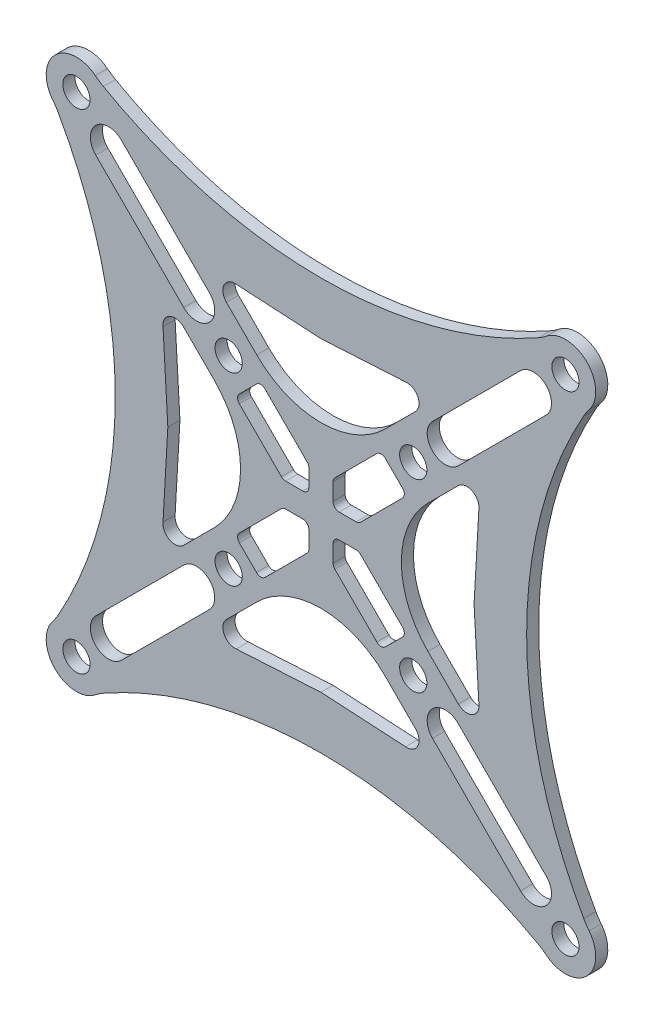
SolidWorks part; units mm, degrees
material "Thornel Mat VMA"
ref_plane "前视基准面" through (0, 0, 0) normal (0, 0, 1) x (1, 0, 0)
ref_plane "上视基准面" through (0, 0, 0) normal (0, 1, 0) x (1, 0, 0)
ref_plane "右视基准面" through (0, 0, 0) normal (1, 0, 0) x (0, 0, -1)
sketch "草图1" plane through (0, 0, 0) normal (0, 0, 1) x (1, 0, 0)
  line L0 (-2.3574, 13.9739) -> (-7.3762, 8.9551)
  line L1 (4.6665, 38.0627) -> (3.2523, 36.6485)
  line L2 (3.2523, 36.6485) -> (1.8381, 35.2343)
  line L3 (1.8381, 33.8201) -> (2.1916, 33.4665)
  line L4 (2.1916, 33.4665) -> (4.9992, 30.659)
  line L5 (4.9992, 30.659) -> (8.7848, 26.8734)
  line L6 (9.4919, 26.5805) -> (12.3203, 26.5805)
  line L7 (13.3203, 27.5805) -> (13.3203, 30.4089)
  line L8 (13.0274, 31.116) -> (9.2418, 34.9016)
  line L9 (9.2418, 34.9016) -> (6.4343, 37.7092)
  line L10 (6.4343, 37.7092) -> (6.0807, 38.0627)
  line L11 (4.6665, 11.0983) -> (3.2523, 12.5125)
  line L12 (3.2523, 12.5125) -> (1.8381, 13.9267)
  line L13 (1.8381, 15.3409) -> (2.1916, 15.6945)
  line L14 (2.1916, 15.6945) -> (4.9992, 18.5021)
  line L15 (4.9992, 18.5021) -> (8.7848, 22.2876)
  line L16 (9.4919, 22.5805) -> (12.3203, 22.5805)
  line L17 (13.3203, 21.5805) -> (13.3203, 18.7521)
  line L18 (13.0274, 18.045) -> (9.2418, 14.2594)
  line L19 (9.2418, 14.2594) -> (6.4343, 11.4518)
  line L20 (6.4343, 11.4518) -> (6.0807, 11.0983)
  line L21 (-3.1117, 1.9059) -> (-17.6553, -12.6377)
  line L22 (-21.898, -8.3951) -> (-7.3543, 6.1485)
  line L23 (-2.3574, 35.1871) -> (-7.3762, 40.2059)
  line L24 (-0.3051, 1.884) -> (4.7137, 6.9028)
  line L25 (52.5385, 57.5561) -> (37.9949, 43.0125)
  line L26 (33.7523, 47.2551) -> (48.2959, 61.7988)
  line L27 (30.9457, 1.884) -> (25.9269, 6.9028)
  line L28 (25.9741, 11.0983) -> (27.3883, 12.5125)
  line L29 (27.3883, 12.5125) -> (28.8025, 13.9267)
  line L30 (28.8025, 15.3409) -> (28.449, 15.6945)
  line L31 (28.449, 15.6945) -> (25.6414, 18.5021)
  line L32 (25.6414, 18.5021) -> (21.8558, 22.2876)
  line L33 (21.1487, 22.5805) -> (18.3203, 22.5805)
  line L34 (17.3203, 21.5805) -> (17.3203, 18.7521)
  line L35 (17.6132, 18.045) -> (21.3987, 14.2594)
  line L36 (21.3987, 14.2594) -> (24.2063, 11.4518)
  line L37 (24.2063, 11.4518) -> (24.5599, 11.0983)
  line L38 (37.9949, 6.1485) -> (52.5385, -8.3951)
  line L39 (48.2959, -12.6377) -> (33.7523, 1.9059)
  line L40 (32.998, 13.9739) -> (38.0168, 8.9551)
  line L41 (21.3987, 34.9016) -> (24.2063, 37.7092)
  line L42 (24.2063, 37.7092) -> (24.5599, 38.0627)
  line L43 (25.9741, 38.0627) -> (27.3883, 36.6485)
  line L44 (27.3883, 36.6485) -> (28.8025, 35.2343)
  line L45 (28.8025, 33.8201) -> (28.449, 33.4665)
  line L46 (28.449, 33.4665) -> (25.6414, 30.659)
  line L47 (25.6414, 30.659) -> (21.8558, 26.8734)
  line L48 (21.1487, 26.5805) -> (18.3203, 26.5805)
  line L49 (17.3203, 27.5805) -> (17.3203, 30.4089)
  line L50 (17.6132, 31.116) -> (21.3987, 34.9016)
  line L51 (32.998, 35.1871) -> (38.0168, 40.2059)
  line L52 (-0.3051, 47.277) -> (4.7137, 42.2582)
  line L53 (30.9457, 47.277) -> (25.9269, 42.2582)
  line L54 (-7.3543, 43.0125) -> (-21.898, 57.5561)
  line L55 (-17.6553, 61.7988) -> (-3.1117, 47.2551)
  arc A0 (1.8381, 35.2343) -> (1.8381, 33.8201) centre (2.5452, 34.5272) ccw
  arc A1 (8.7848, 26.8734) -> (9.4919, 26.5805) centre (9.4919, 27.5805) ccw
  arc A2 (12.3203, 26.5805) -> (13.3203, 27.5805) centre (12.3203, 27.5805) ccw
  arc A3 (13.3203, 30.4089) -> (13.0274, 31.116) centre (12.3203, 30.4089) ccw
  arc A4 (6.0807, 38.0627) -> (4.6665, 38.0627) centre (5.3736, 37.3556) ccw
  circle A5 centre (-25.0799, -15.8197) radius 2.25
  arc A6 (1.8381, 15.3409) -> (1.8381, 13.9267) centre (2.5452, 14.6338) ccw
  arc A7 (9.4919, 22.5805) -> (8.7848, 22.2876) centre (9.4919, 21.5805) ccw
  arc A8 (13.3203, 21.5805) -> (12.3203, 22.5805) centre (12.3203, 21.5805) ccw
  arc A9 (13.0274, 18.045) -> (13.3203, 18.7521) centre (12.3203, 18.7521) ccw
  arc A10 (4.6665, 11.0983) -> (6.0807, 11.0983) centre (5.3736, 11.8054) ccw
  arc A11 (-21.898, -8.3951) -> (-17.6553, -12.6377) centre (-19.7766, -10.5164) ccw
  arc A12 (-3.1117, 1.9059) -> (-7.3543, 6.1485) centre (-5.233, 4.0272) ccw
  arc A13 (-28.9897, -12.7031) -> (-21.9633, -19.7295) centre (-25.0799, -15.8197) ccw
  arc A14 (15.3203, 11.2962) -> (4.7137, 6.9028) centre (15.3203, -3.7038) ccw
  arc A15 (-0.3051, 1.884) -> (1.3391, -1.5169) centre (1.1091, 0.4698) ccw
  arc A16 (-10.7771, 10.5993) -> (-7.3762, 8.9551) centre (-8.7904, 10.3693) ccw
  circle A17 centre (0.0703, 9.3305) radius 2.25
  arc A18 (2.036, 24.5805) -> (-2.3574, 35.1871) centre (-12.964, 24.5805) ccw
  arc A19 (-2.3574, 13.9739) -> (2.036, 24.5805) centre (-12.964, 24.5805) ccw
  arc A20 (52.5385, 57.5561) -> (48.2959, 61.7988) centre (50.4172, 59.6774) ccw
  arc A21 (33.7523, 47.2551) -> (37.9949, 43.0125) centre (35.8736, 45.1338) ccw
  arc A22 (38.0168, 8.9551) -> (41.4177, 10.5993) centre (39.431, 10.3693) ccw
  arc A23 (25.9269, 6.9028) -> (15.3203, 11.2962) centre (15.3203, -3.7038) ccw
  arc A24 (28.8025, 13.9267) -> (28.8025, 15.3409) centre (28.0954, 14.6338) ccw
  arc A25 (21.8558, 22.2876) -> (21.1487, 22.5805) centre (21.1487, 21.5805) ccw
  arc A26 (18.3203, 22.5805) -> (17.3203, 21.5805) centre (18.3203, 21.5805) ccw
  arc A27 (17.3203, 18.7521) -> (17.6132, 18.045) centre (18.3203, 18.7521) ccw
  arc A28 (24.5599, 11.0983) -> (25.9741, 11.0983) centre (25.267, 11.8054) ccw
  arc A29 (29.3015, -1.5169) -> (30.9457, 1.884) centre (29.5315, 0.4698) ccw
  arc A30 (48.2959, -12.6377) -> (52.5385, -8.3951) centre (50.4172, -10.5164) ccw
  arc A31 (37.9949, 6.1485) -> (33.7523, 1.9059) centre (35.8736, 4.0272) ccw
  circle A32 centre (30.5703, 9.3305) radius 2.25
  circle A33 centre (55.7205, -15.8197) radius 2.25
  arc A34 (52.6039, -19.7295) -> (59.6303, -12.7031) centre (55.7205, -15.8197) ccw
  arc A35 (25.9741, 38.0627) -> (24.5599, 38.0627) centre (25.267, 37.3556) ccw
  arc A36 (28.8025, 33.8201) -> (28.8025, 35.2343) centre (28.0954, 34.5272) ccw
  arc A37 (21.1487, 26.5805) -> (21.8558, 26.8734) centre (21.1487, 27.5805) ccw
  arc A38 (17.3203, 27.5805) -> (18.3203, 26.5805) centre (18.3203, 27.5805) ccw
  arc A39 (17.6132, 31.116) -> (17.3203, 30.4089) centre (18.3203, 30.4089) ccw
  arc A40 (32.998, 35.1871) -> (28.6046, 24.5805) centre (43.6046, 24.5805) ccw
  arc A41 (28.6046, 24.5805) -> (32.998, 13.9739) centre (43.6046, 24.5805) ccw
  circle A42 centre (55.7205, 64.9807) radius 2.25
  arc A43 (-17.6553, 61.7988) -> (-21.898, 57.5561) centre (-19.7766, 59.6774) ccw
  arc A44 (-7.3543, 43.0125) -> (-3.1117, 47.2551) centre (-5.233, 45.1338) ccw
  circle A45 centre (30.5703, 39.8305) radius 2.25
  arc A46 (59.6303, 61.8641) -> (52.6039, 68.8905) centre (55.7205, 64.9807) ccw
  arc A47 (-7.3762, 40.2059) -> (-10.7771, 38.5617) centre (-8.7904, 38.7917) ccw
  arc A48 (30.9457, 47.277) -> (29.3015, 50.6779) centre (29.5315, 48.6912) ccw
  arc A49 (4.7137, 42.2582) -> (15.3203, 37.8648) centre (15.3203, 52.8648) ccw
  arc A50 (15.3203, 37.8648) -> (25.9269, 42.2582) centre (15.3203, 52.8648) ccw
  circle A51 centre (0.0703, 39.8305) radius 2.25
  arc A52 (1.3391, 50.6779) -> (-0.3051, 47.277) centre (1.1091, 48.6912) ccw
  arc A53 (-21.9633, 68.8905) -> (-28.9897, 61.8641) centre (-25.0799, 64.9807) ccw
  arc A54 (41.4177, 38.5617) -> (38.0168, 40.2059) centre (39.431, 38.7917) ccw
  circle A55 centre (-25.0799, 64.9807) radius 2.25
  arc A56 (-28.0953, -11.3755) -> (-28.0953, 60.5365) centre (-91.9643, 24.5805) ccw
  arc A57 (51.2763, -18.8351) -> (-20.6357, -18.8351) centre (15.3203, -82.704) ccw
  arc A58 (-20.6357, 67.9961) -> (51.2763, 67.9961) centre (15.3203, 131.8651) ccw
  arc A59 (-21.9633, 68.8905) -> (-20.6357, 67.9961) centre (-15.73, 76.7102) ccw
  arc A60 (-28.0953, 60.5365) -> (-28.9897, 61.8641) centre (-36.8094, 55.6308) ccw
  arc A61 (-28.9897, -12.7031) -> (-28.0953, -11.3755) centre (-36.8094, -6.4698) ccw
  arc A62 (-20.6357, -18.8351) -> (-21.9633, -19.7295) centre (-15.73, -27.5491) ccw
  arc A63 (51.2763, 67.9961) -> (52.6039, 68.8905) centre (46.3706, 76.7102) ccw
  arc A64 (59.6303, 61.8641) -> (58.7359, 60.5365) centre (67.4499, 55.6308) ccw
  arc A65 (52.6039, -19.7295) -> (51.2763, -18.8351) centre (46.3706, -27.5491) ccw
  arc A66 (58.7359, -11.3755) -> (59.6303, -12.7031) centre (67.4499, -6.4698) ccw
  arc A67 (58.7359, 60.5365) -> (58.7359, -11.3755) centre (122.6048, 24.5805) ccw
  spline S0 degree 3 poles (1.3391, -1.5169) (5.9995, -1.2512) (10.6599, -0.9854) (15.3203, -0.7197) knots 0 0 0 0 1.400387 1.400387 1.400387 1.400387
  spline S1 degree 3 poles (-10.7771, 38.5617) (-10.5114, 33.9013) (-10.2456, 29.2409) (-9.9799, 24.5805) knots 0 0 0 0 1.400387 1.400387 1.400387 1.400387
  spline S2 degree 3 poles (-10.7771, 10.5993) (-10.5114, 15.2597) (-10.2456, 19.9201) (-9.9799, 24.5805) knots 0 0 0 0 1.400387 1.400387 1.400387 1.400387
  spline S3 degree 3 poles (29.3015, -1.5169) (24.6411, -1.2512) (19.9807, -0.9854) (15.3203, -0.7197) knots 0 0 0 0 1.400387 1.400387 1.400387 1.400387
  spline S4 degree 3 poles (41.4177, 10.5993) (41.152, 15.2597) (40.8862, 19.9201) (40.6205, 24.5805) knots 0 0 0 0 1.400387 1.400387 1.400387 1.400387
  spline S5 degree 3 poles (41.4177, 38.5617) (41.152, 33.9013) (40.8862, 29.2409) (40.6205, 24.5805) knots 0 0 0 0 1.400387 1.400387 1.400387 1.400387
  spline S6 degree 3 poles (1.3391, 50.6779) (5.9995, 50.4122) (10.6599, 50.1464) (15.3203, 49.8807) knots 0 0 0 0 1.400387 1.400387 1.400387 1.400387
  spline S7 degree 3 poles (29.3015, 50.6779) (24.6411, 50.4122) (19.9807, 50.1464) (15.3203, 49.8807) knots 0 0 0 0 1.400387 1.400387 1.400387 1.400387
  dimension "D1" = 6
extrude "凸台-拉伸1" add sketch "草图1" along normal blind 2
